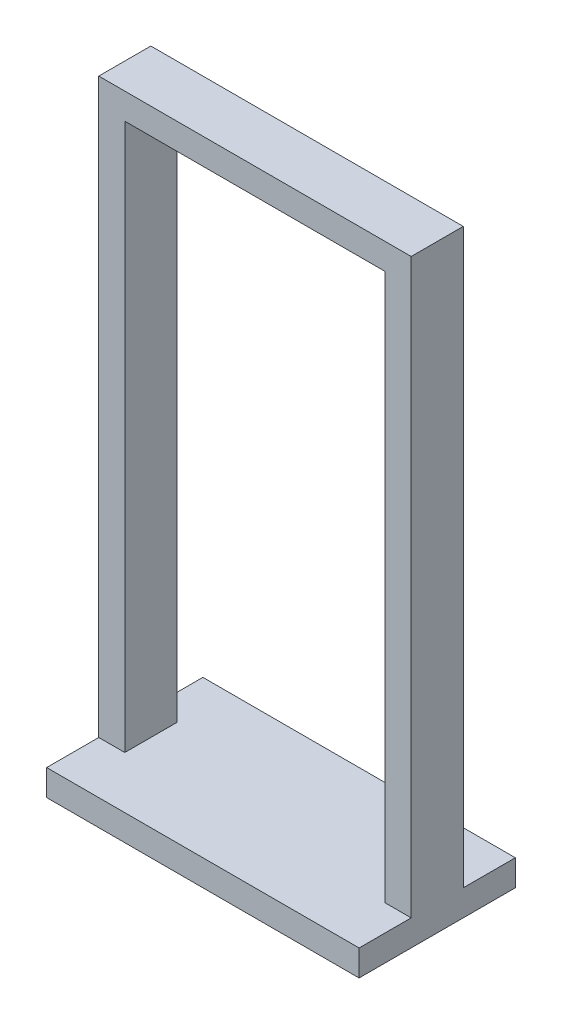
SolidWorks part; units mm, degrees
ref_plane "Plano frontal" through (0, 0, 0) normal (0, 0, 1) x (1, 0, 0)
ref_plane "Plano superior" through (0, 0, 0) normal (0, 1, 0) x (1, 0, 0)
ref_plane "Plano direito" through (0, 0, 0) normal (1, 0, 0) x (0, 0, -1)
sketch "Esboço1" plane through (0, 0, 0) normal (0, 0, 1) x (1, 0, 0)
  line L1 (-500, -1050) -> (500, -1050)
  line L2 (-500, -1050) -> (-500, 1050)
  line L3 (-500, 1050) -> (500, 1050)
  line L4 (500, -1050) -> (500, 1050)
  line L5 (0, 1050) -> (0, -1050) construction
  line L6 (-500, 0) -> (500, 0) construction
  point P0 (0, 0)
  dimension "LARGURA_VAO" = 1000
  dimension "ALTURA_VAO" = 2100
extrude "Extrusão-Fina1" add sketch "Esboço1" along normal mid plane 200 thin
sketch "Esboço2" plane through (0, 0, 100) normal (0, 0, 1) x (1, 0, 0)
  line L0 (-500, -1050) -> (500, -1050) construction
  line L1 (-600, -1150) -> (600, -1150)
  line L2 (-600, -1150) -> (-600, -1050)
  line L3 (-600, -1050) -> (600, -1050)
  line L4 (600, -1150) -> (600, -1050)
  line L5 (0, -1050) -> (0, -1150) construction
  line L6 (-600, -1100) -> (600, -1100) construction
  line L7 (600, -1150) -> (600, 1150) construction
  point P148 (0, -1100)
extrude "Ressalto-extrusão1" add sketch "Esboço2" along normal blind 200 and the other way offset from surface (400 mm away) 200 other way up to face at (0, 0, -100)
sketch "Esboço3" plane through (0, 1050, 0) normal (0, -1, 0) x (1, 0, 0)
  line L1 (285, 82.5) -> (355, 82.5)
  line L2 (285, 82.5) -> (285, 65.5)
  line L3 (285, 65.5) -> (355, 65.5)
  line L4 (355, 82.5) -> (355, 65.5)
  line L5 (320, 65.5) -> (320, 82.5) construction
  line L6 (285, 74) -> (355, 74) construction
  point P0 (320, 74)
  dimension "D1" = 17
  dimension "D2" = 70
extrude "Corte-extrusão1" cut sketch "Esboço3" against normal blind 30 contours L2 L3 L4 L1
